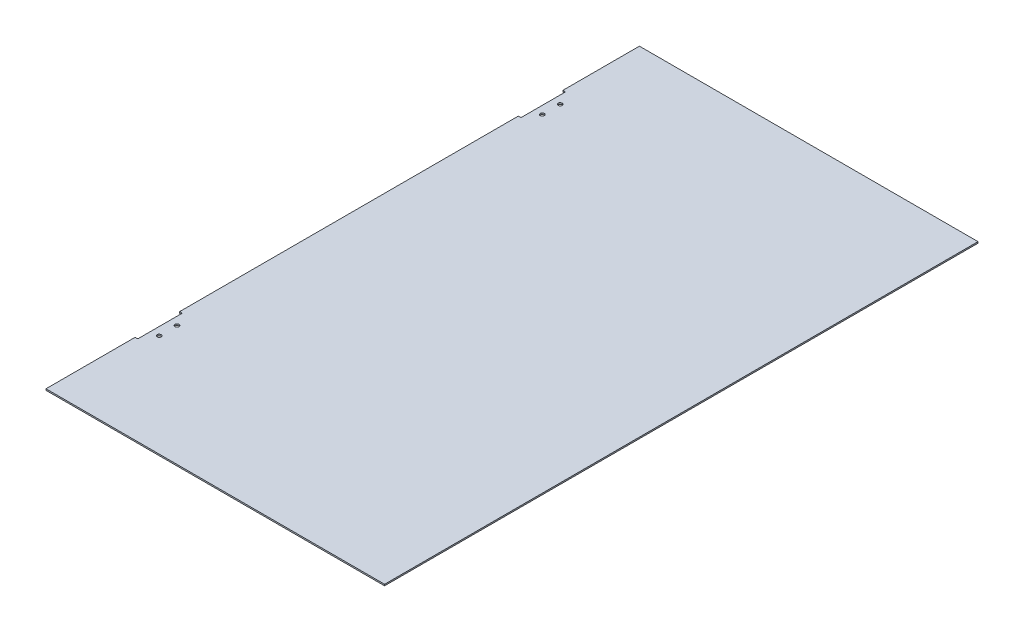
SolidWorks part; units mm, degrees
ref_plane "Front Plane" through (0, 0, 0) normal (0, 0, 1) x (1, 0, 0)
ref_plane "Top Plane" through (0, 0, 0) normal (0, 1, 0) x (1, 0, 0)
ref_plane "Right Plane" through (0, 0, 0) normal (1, 0, 0) x (0, 0, -1)
sketch "Sketch1" plane through (0, 0, 0) normal (0, 1, 0) x (1, 0, 0)
  line L0 (65.3263, 149.0698) -> (95.3263, 149.0698)
  line L1 (-94.6737, 149.0698) -> (-64.6737, 149.0698)
  line L2 (-94.6737, 149.0698) -> (-94.6737, -183.9302)
  line L3 (-94.6737, -183.9302) -> (95.3263, -183.9302)
  line L4 (95.3263, 149.0698) -> (95.3263, -183.9302)
  line L13 (-39.6737, 149.0698) -> (40.3263, 149.0698)
  line L14 (-64.6737, 149.0698) -> (-39.6737, 149.0698)
  line L15 (65.3263, 149.0698) -> (40.3263, 149.0698)
  point P4 (-64.6737, 149.0698)
  point P5 (-94.6737, 149.0698)
  point P15 (65.3263, 149.0698)
  point P16 (40.3263, 149.0698)
  dimension "D1" = 333
  dimension "D2" = 190
  dimension "D6" = 30
extrude "Panel" add sketch "Sketch1" along normal blind 0.79
ref_plane "Length" through (0.3263, 0, 0) normal (-1, 0, 0) x (0, 0, 1)
ref_plane "Width " through (0, 0, 13.9302) normal (0, 0, 1) x (1, 0, 0)
sketch "Sketch3" plane through (0, 0.79, 0) normal (0, 1, 0) x (1, 0, 0)
  line L23 (-94.6737, 149.0698) -> (-94.6737, -183.9302) construction
  line L30 (-94.6737, -128.9302) -> (-84.6737, -128.9302) construction
  line L31 (-94.6737, -128.9302) -> (-94.6737, -113.9302) construction
  line L32 (-94.6737, -113.9302) -> (-84.6737, -113.9302) construction
  line L33 (-84.6737, -128.9302) -> (-84.6737, -113.9302) construction
  line L34 (-94.6737, -108.9302) -> (-93.6737, -108.9302)
  line L35 (-94.6737, -108.9302) -> (-94.6737, -133.9302)
  line L36 (-94.6737, -133.9302) -> (-93.6737, -133.9302)
  line L37 (-93.1737, -109.4302) -> (-93.1737, -133.4302)
  circle A4 centre (-88.6737, -116.4302) radius 1.125
  circle A5 centre (-88.6737, -126.4302) radius 1.125
  arc A6 (-93.1737, -133.4302) -> (-93.6737, -133.9302) centre (-93.6737, -133.4302) cw
  arc A7 (-93.1737, -109.4302) -> (-93.6737, -108.9302) centre (-93.6737, -109.4302) ccw
  point P0 (-94.6737, -183.9302)
  point P1 (-94.6737, -128.9302)
  point P19 (-93.1737, -133.9302)
  point P22 (-93.1737, -108.9302)
  dimension "D5" = 5
  dimension "D9" = 2.25
  dimension "D11" = 4
  dimension "D13" = 0.5
  dimension "D12" = 2.25
  dimension "D1" = 55
  dimension "D2" = 15
  dimension "D3" = 10
  dimension "D4" = 1.5
  dimension "D6" = 5
  dimension "D7" = 4
  dimension "D8" = 2.5
  dimension "D10" = 2.5
extrude "Hinge Mount" cut sketch "Sketch3" against normal blind 0.79
mirror "Mirror1" about plane through (0, 0, 13.9302) normal (0, 0, 1) of "Hinge Mount"
sketch "Text" plane through (0, 0.79, 0) normal (0, 1, 0) x (1, 0, 0)
  text T0 "<b>Top Outside (PCB)</b>" font "Century Gothic" height 5
